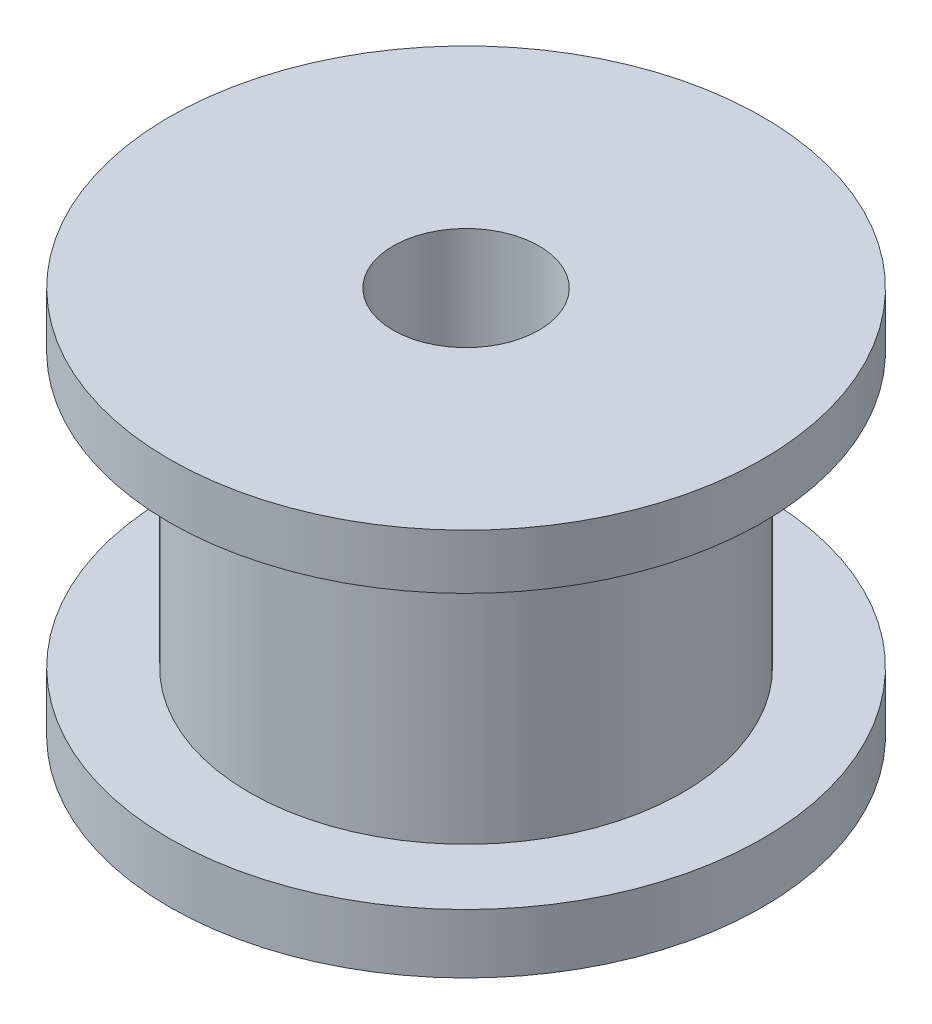
SolidWorks part; units mm, degrees
ref_plane "前视基准面" through (0, 0, 0) normal (0, 0, 1) x (1, 0, 0)
ref_plane "上视基准面" through (0, 0, 0) normal (0, 1, 0) x (1, 0, 0)
ref_plane "右视基准面" through (0, 0, 0) normal (1, 0, 0) x (0, 0, -1)
sketch "草图1" plane through (0, 0, 0) normal (0, 0, 1) x (1, 0, 0)
  line L0 (0, 0) -> (-6.5, 0)
  line L1 (-6.5, 0) -> (-6.5, 1.3)
  line L2 (-6.5, 1.3) -> (-4.75, 1.3)
  line L3 (-4.75, 1.3) -> (-4.75, 7.3)
  line L4 (-4.75, 7.3) -> (-6.5, 7.3)
  line L5 (-6.5, 7.3) -> (-6.5, 8.5)
  line L6 (-6.5, 8.5) -> (0, 8.5)
  line L7 (0, 8.5) -> (0, 0)
  dimension "D1" = 8.5
  dimension "D2" = 6
  dimension "D3" = 6.5
  dimension "D4" = 4.75
  dimension "D5" = 1.2
revolve "旋转1" add sketch "草图1" angle 360 about L7
sketch "草图2" plane through (0, 8.5, 0) normal (0, 1, 0) x (1, 0, 0)
  circle A0 centre (0, 0) radius 1.6
  dimension "D1" = 3.2
extrude "切除-拉伸1" cut sketch "草图2" against normal blind 10
